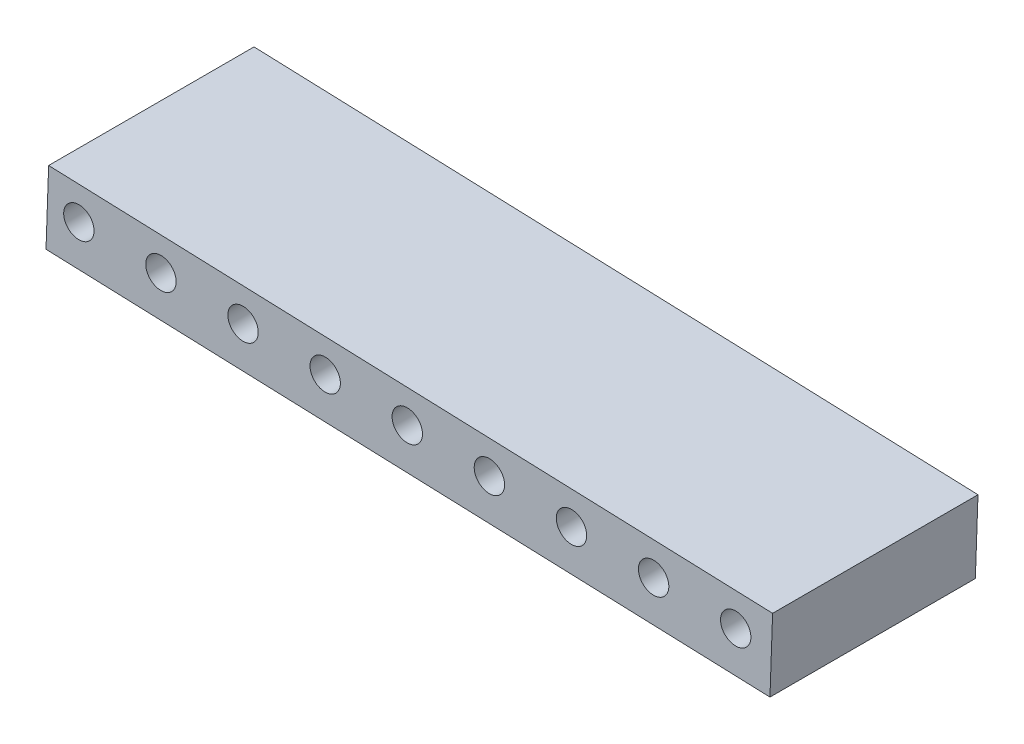
SolidWorks part; units mm, degrees
ref_plane "前视基准面" through (0, 0, 0) normal (0, 0, 1) x (1, 0, 0)
ref_plane "上视基准面" through (0, 0, 0) normal (0, 1, 0) x (1, 0, 0)
ref_plane "右视基准面" through (0, 0, 0) normal (1, 0, 0) x (0, 0, -1)
other "Configuration Table"
sketch "草图1" plane through (0, 0, 0) normal (0, 0, 1) x (1, 0, 0)
  line L0 (0, 0) -> (140, 0)
  line L1 (0, 35) -> (140, 25)
  line L2 (0, -35) -> (140, -25)
  circle A0 centre (0, 0) radius 35
  circle A1 centre (140, 0) radius 25
  dimension "D1" = 70
  dimension "D3" = 50
  dimension "D2" = 140
extrude "凸台-拉伸3" add sketch "草图1" along normal blind 5
sketch "草图4" plane through (0, 0, 5) normal (0, 0, 1) x (1, 0, 0)
  line L1 (-5, -5) -> (5, -5)
  line L2 (-5, -5) -> (-5, 5)
  line L3 (-5, 5) -> (5, 5)
  line L4 (5, -5) -> (5, 5)
  line L5 (-5, -5) -> (5, 5) construction
  line L6 (-5, 5) -> (5, -5) construction
  line L7 (135, -5) -> (145, -5)
  line L8 (135, -5) -> (135, 5)
  line L9 (135, 5) -> (145, 5)
  line L10 (145, -5) -> (145, 5)
  line L11 (135, -5) -> (145, 5) construction
  line L12 (135, 5) -> (145, -5) construction
  circle A0 centre (0, 0) radius 4
  circle A1 centre (-5, 5) radius 1.5
  circle A2 centre (5, 5) radius 1.5
  circle A3 centre (5, -5) radius 1.5
  circle A4 centre (-5, -5) radius 1.5
  circle A5 centre (140, 0) radius 4
  circle A6 centre (135, 5) radius 1.5
  circle A7 centre (145, 5) radius 1.5
  circle A8 centre (145, -5) radius 1.5
  circle A9 centre (135, -5) radius 1.5
  dimension "D1" = 8
  dimension "D4" = 3
  dimension "D6" = 8
  dimension "D9" = 3
  dimension "D2" = 10
  dimension "D3" = 10
  dimension "D7" = 10
  dimension "D8" = 10
  dimension "D5" = 4
  dimension "D10" = 4
extrude "切除-拉伸3" cut sketch "草图4" against normal blind 5 contours A5 | A0 | L2 A4 L1 | L1 A4 L2 | A6 | A9 | A8 | A7 | A1 | A2 | A3
sketch "草图5" plane through (0, 0, 5) normal (0, 0, 1) x (1, 0, 0)
  circle A0 centre (0, 0) radius 11
  circle A1 centre (140, 0) radius 11
  dimension "D1" = 22
  dimension "D2" = 22
extrude "切除-拉伸4" cut sketch "草图5" against normal blind 2
sketch "草图6" plane through (0, 0, 5) normal (0, 0, 1) x (1, 0, 0)
  circle A0 centre (0, 0) radius 30
  circle A1 centre (0, 30) radius 1.5
  circle A2 centre (15, 25.9808) radius 1.5
  circle A3 centre (25.9808, 15) radius 1.5
  circle A4 centre (30, 0) radius 1.5
  circle A5 centre (25.9808, -15) radius 1.5
  circle A6 centre (15, -25.9808) radius 1.5
  circle A7 centre (0, -30) radius 1.5
  circle A8 centre (-15, -25.9808) radius 1.5
  circle A9 centre (-25.9808, -15) radius 1.5
  circle A10 centre (-30, 0) radius 1.5
  circle A11 centre (-25.9808, 15) radius 1.5
  circle A12 centre (-15, 25.9808) radius 1.5
  circle A13 centre (140, 0) radius 20
  circle A14 centre (140, 20) radius 1.5
  circle A15 centre (150, 17.3205) radius 1.5
  circle A16 centre (157.3205, 10) radius 1.5
  circle A17 centre (160, 0) radius 1.5
  circle A18 centre (157.3205, -10) radius 1.5
  circle A19 centre (150, -17.3205) radius 1.5
  circle A20 centre (140, -20) radius 1.5
  circle A21 centre (130, -17.3205) radius 1.5
  circle A22 centre (122.6795, -10) radius 1.5
  circle A23 centre (120, 0) radius 1.5
  circle A24 centre (122.6795, 10) radius 1.5
  circle A25 centre (130, 17.3205) radius 1.5
  point P29 (0, 0)
  dimension "D1" = 60
  dimension "D2" = 3
  dimension "D4" = 40
  dimension "D5" = 3
  dimension "D3" = 12
  dimension "D6" = 12
extrude "切除-拉伸6" cut sketch "草图6" against normal through all contours A0 A12 | A11 | A1 | A2 | A3 | A4 | A5 | A6 | A7 | A8 | A9 | A10 | A25 | A14 | A15 | A16 | A17 | A18 | A19 | A20 | A21 | A22 | A23 | A24
sketch "草图7" plane through (0, 0, 5) normal (0, 0, 1) x (1, 0, 0)
  line L0 (140, 25) -> (0, 20)
  line L1 (140, -25) -> (0, -20)
  circle A0 centre (0, 0) radius 20
  circle A1 centre (140, 0) radius 25
  circle M1 centre (15, -25.9808) radius 1.5
  circle M2 centre (0, -30) radius 1.5
  circle M3 centre (-15, -25.9808) radius 1.5
  circle M4 centre (-25.9808, -15) radius 1.5
  circle M5 centre (-30, 0) radius 1.5
  circle M20 centre (15, 25.9808) radius 1.5
  circle M21 centre (-15, 25.9808) radius 1.5
  circle M22 centre (-25.9808, 15) radius 1.5
  circle M23 centre (0, 30) radius 1.5
  line M27 (0, -35) -> (140, -25)
  line M29 (140, 25) -> (0, 35)
  arc M30 (0, 35) -> (0, -35) centre (0, 0) ccw
  dimension "D1" = 40
extrude "切除-拉伸7" cut sketch "草图7" against normal blind 10 contours A1 L1 A0 L0 M29 M30 M27 M1 M3 M5 M21 M23 M22 M20 M4 M2
sketch "草图8" plane through (0, 0, 5) normal (0, 0, 1) x (1, 0, 0)
  circle A1 centre (0, 0) radius 11
extrude "切除-拉伸8" cut sketch "草图8" against normal blind 10
sketch "草图9" plane through (0, 0, 5) normal (0, 0, 1) x (1, 0, 0)
  circle A0 centre (0, 0) radius 15
  circle A1 centre (0, 15) radius 1.5
  circle A2 centre (10.6066, 10.6066) radius 1.5
  circle A3 centre (15, 0) radius 1.5
  circle A4 centre (10.6066, -10.6066) radius 1.5
  circle A5 centre (0, -15) radius 1.5
  circle A6 centre (-10.6066, -10.6066) radius 1.5
  circle A7 centre (-15, 0) radius 1.5
  circle A8 centre (-10.6066, 10.6066) radius 1.5
  dimension "D1" = 30
  dimension "D2" = 3
  dimension "D3" = 8
extrude "切除-拉伸9" cut sketch "草图9" against normal blind 10 contours A0 A4 | A2 | A3 | A5 | A6 | A7 | A8 | A1
sketch "草图10" plane through (0, 0, 3) normal (0, 0, 1) x (1, 0, 0)
  circle A0 centre (140, 0) radius 5
  dimension "D1" = 10
extrude "切除-拉伸10" cut sketch "草图10" against normal blind 10
sketch "草图11" plane through (0, 0, 5) normal (0, 0, 1) x (1, 0, 0)
  line L0 (140, 0) -> (110, 0)
  line L1 (140, 0) -> (130, 0)
  line L2 (110, 0) -> (105.5, 0)
  line L3 (150, -10) -> (110, -10)
  line L4 (150, -10) -> (150, 10)
  line L5 (150, 10) -> (110, 10)
  line L6 (110, -10) -> (110, 10)
  line L7 (150, -10) -> (110, 10) construction
  line L8 (150, 10) -> (110, -10) construction
  line L9 (105.5, 0) -> (105.5, 5)
  line L10 (130, -1000) -> (130, 49000) construction
  circle A0 centre (105.5, 5) radius 2
  circle A1 centre (105.5, -5) radius 2
  circle A2 centre (154.5, -5) radius 2
  circle A3 centre (154.5, 5) radius 2
  dimension "D6" = 4
  dimension "D1" = 30
  dimension "D2" = 10
  dimension "D3" = 20
  dimension "D4" = 4.5
  dimension "D5" = 5
extrude "切除-拉伸11" cut sketch "草图11" against normal blind 10
sketch "草图12" plane through (0, 0, 5) normal (0, 0, 1) x (1, 0, 0)
  line L0 (110, 10) -> (44831.3595, -22350.6798) construction
  line L1 (150, 10) -> (-44571.3595, -22350.6798) construction
  line L3 (109.5, -11) -> (150.5, -11)
  line L4 (109.5, -11) -> (109.5, 11)
  line L5 (109.5, 11) -> (150.5, 11)
  line L6 (150.5, -11) -> (150.5, 11)
  line L7 (109.5, -11) -> (150.5, 11) construction
  line L8 (109.5, 11) -> (150.5, -11) construction
  point P8 (130, 0)
  dimension "D1" = 41
  dimension "D2" = 22
extrude "切除-拉伸12" cut sketch "草图12" against normal blind 10
sketch "草图13" plane through (0, 0, 5) normal (0, 0, 1) x (1, 0, 0)
  line L0 (0.1785, -15.0032) -> (138.395, -19.9395)
  line L1 (0, -20) -> (138.2166, -24.9363)
  circle A0 centre (0, -15) radius 1.5
  circle A1 centre (9.9936, -15.3569) radius 1.5
  circle A2 centre (19.9873, -15.7138) radius 1.5
  circle A3 centre (29.9809, -16.0707) radius 1.5
  circle A4 centre (39.9745, -16.4277) radius 1.5
  circle A5 centre (49.9681, -16.7846) radius 1.5
  circle A6 centre (59.9618, -17.1415) radius 1.5
  circle A7 centre (69.9554, -17.4984) radius 1.5
  circle A8 centre (79.949, -17.8553) radius 1.5
  circle A9 centre (89.9427, -18.2122) radius 1.5
  circle A10 centre (99.9363, -18.5692) radius 1.5
  circle A11 centre (109.9299, -18.9261) radius 1.5
  circle A12 centre (119.9235, -19.283) radius 1.5
  circle A13 centre (129.9172, -19.6399) radius 1.5
  circle A14 centre (139.9108, -19.9968) radius 1.5
  circle M27 centre (130, -17.3205) radius 1.5
  dimension "D1" = 5
  dimension "D2" = 15
extrude "切除-拉伸13" cut sketch "草图13" against normal blind 10 contours L0 A1 | L0 A1 | L0 A13 | A13 L0 M27 | A2 | A3 | A4 | A5 | A6 | A7 | A9 | A8 | A10 | A11 | A12
sketch "草图14" plane through (0, 0, 5) normal (0, 0, 1) x (1, 0, 0)
  circle A0 centre (130, -17.3205) radius 1.5
  circle A1 centre (129.9172, -19.6399) radius 1.5
extrude "凸台-拉伸4" add sketch "草图14" against normal blind 5 contours A1 A0
sketch "草图15" plane through (0, 0, 5) normal (0, 0, 1) x (1, 0, 0)
  circle A0 centre (25.9808, 15) radius 1.5
  circle A1 centre (30, 0) radius 1.5
  circle A2 centre (25.9808, -15) radius 1.5
extrude "凸台-拉伸6" add sketch "草图15" against normal blind 5
sketch "草图16" plane through (0, 0, 5) normal (0, 0, 1) x (1, 0, 0)
  line L0 (0, 20) -> (140, 25)
  line L1 (0.1785, 15.0032) -> (140.1785, 20.0032)
  arc A0 (138.2166, -24.9363) -> (138.2166, 24.9363) centre (140, 0) ccw construction
  circle A1 centre (0, 15) radius 1.5
  circle A2 centre (9.9936, 15.3569) radius 1.5
  circle A3 centre (19.9873, 15.7138) radius 1.5
  circle A4 centre (29.9809, 16.0707) radius 1.5
  circle A5 centre (39.9745, 16.4277) radius 1.5
  circle A6 centre (49.9681, 16.7846) radius 1.5
  circle A7 centre (59.9618, 17.1415) radius 1.5
  circle A8 centre (69.9554, 17.4984) radius 1.5
  circle A9 centre (79.949, 17.8553) radius 1.5
  circle A10 centre (89.9427, 18.2122) radius 1.5
  circle A11 centre (99.9363, 18.5692) radius 1.5
  circle A12 centre (109.9299, 18.9261) radius 1.5
  circle A13 centre (119.9235, 19.283) radius 1.5
  circle A14 centre (129.9172, 19.6399) radius 1.5
  circle A15 centre (139.9108, 19.9968) radius 1.5
  dimension "D1" = 5
  dimension "D2" = 15
extrude "切除-拉伸14" cut sketch "草图16" against normal blind 5 contours L1 A6 | L1 A6 | L1 A7 | L1 A7 | L1 A8 | L1 A8 | A2 | A3 | A4 | A5 | A9 | A10 | A11 | A12 | A13 | A14
sketch "草图17" plane through (0, 0, 5) normal (0, 0, 1) x (1, 0, 0)
  circle A0 centre (130, 17.3205) radius 1.5
  circle A1 centre (129.9172, 19.6399) radius 1.5
extrude "凸台-拉伸7" add sketch "草图17" against normal blind 5 contours A1 A0
sketch "草图18" plane through (0, 0, 5) normal (0, 0, 1) x (1, 0, 0)
  line L2 (138.5735, 14.9427) -> (0.3569, 10.0064)
  line L3 (138.5735, 14.9427) -> (0.3569, 10.0064)
  line L5 (138.5735, -14.9427) -> (0.3569, -10.0064)
  line L6 (138.5735, -14.9427) -> (0.3569, -10.0064)
  circle A0 centre (0, 0) radius 25
  circle A1 centre (0, 0) radius 100
  dimension "D1" = 50
  dimension "D2" = 200
  dimension "D3" = 10
  dimension "D4" = 10
extrude "切除-拉伸15" cut sketch "草图18" against normal blind 5 contours L6 A1 L3 A0
sketch "草图19" plane through (0, 0, 5) normal (0, 0, 1) x (1, 0, 0)
  line L2 (99.0445, 14.5316) -> (22.5117, 11.7983)
  line L3 (134.9707, 15.8146) -> (6.5499, 11.2282)
  line L4 (16.3089, 11.5767) -> (15.9877, 20.571)
  line L5 (99.0445, -14.5316) -> (22.5117, -11.7983)
  line L6 (134.4063, -15.7945) -> (10.6063, -11.3731)
  line L7 (138.2166, 24.9363) -> (0, 20) construction
  line L8 (16.3089, -11.5767) -> (15.9877, -20.571)
  line L9 (138.2166, -24.9363) -> (0, -20) construction
  line L10 (15.9877, -20.571) -> (0, -20)
  line L11 (15.9877, 20.571) -> (0, 20)
  circle A1 centre (140, 0) radius 16.7558
  circle A2 centre (0, 0) radius 20
  dimension "D1" = 1
  dimension "D2" = 1
extrude "切除-拉伸19" cut sketch "草图19" against normal blind 5
sketch "草图21" plane through (0, 0, 5) normal (0, 0, 1) x (1, 0, 0)
  line L0 (134.4063, 15.7945) -> (134.0851, 24.7888)
  line L1 (138.2166, 24.9363) -> (15.9877, 20.571) construction
  line L2 (134.4063, -15.7945) -> (134.0851, -24.7888)
  line L3 (138.2166, -24.9363) -> (15.9877, -20.571) construction
  circle A0 centre (140, 0) radius 25
  arc M1 (156.2593, 4.0487) -> (156.2593, -4.0487) centre (140, 0) cw
  arc M2 (156.2593, -4.0487) -> (155.299, -6.8335) centre (154.5, -5) cw
  arc M3 (155.299, -6.8335) -> (134.4063, -15.7945) centre (140, 0) cw
  line M6 (15.9877, -20.571) -> (138.2166, -24.9363)
  arc M7 (138.2166, -24.9363) -> (138.2166, 24.9363) centre (140, 0) ccw
  line M8 (138.2166, 24.9363) -> (15.9877, 20.571)
  arc M11 (134.4063, 15.7945) -> (155.299, 6.8335) centre (140, 0) cw
  arc M12 (155.299, 6.8335) -> (156.2593, 4.0487) centre (154.5, 5) cw
  circle M37 centre (140, 20) radius 1.5
  circle M38 centre (150, 17.3205) radius 1.5
  circle M39 centre (157.3205, 10) radius 1.5
  circle M40 centre (160, 0) radius 1.5
  circle M41 centre (157.3205, -10) radius 1.5
  circle M42 centre (150, -17.3205) radius 1.5
  circle M43 centre (140, -20) radius 1.5
extrude "切除-拉伸20" cut sketch "草图21" against normal blind 5 contours A0 L0 L2 M7 M11 M12 M1 M2 M3 M38 M40 M42 M43 M41 M39 M37 | A0 L0 M8 | A0 L2 M6
sketch "草图22" plane through (0, 0, 0) normal (0, 0, -1) x (-1, 0, 0)
  line L0 (-134.0851, 24.7888) -> (-134.4063, 15.7945)
  line L1 (-134.4063, 15.7945) -> (-16.3089, 11.5767)
  line L2 (-16.3089, 11.5767) -> (-15.9877, 20.571)
  line L3 (-15.9877, 20.571) -> (-134.0851, 24.7888)
  line L4 (-134.4063, -15.7945) -> (-134.0851, -24.7888)
  line L5 (-134.0851, -24.7888) -> (-15.9877, -20.571)
  line L6 (-15.9877, -20.571) -> (-16.3089, -11.5767)
  line L7 (-16.3089, -11.5767) -> (-134.4063, -15.7945)
extrude "凸台-拉伸8" add sketch "草图22" along normal blind 10
sketch "草图23" plane through (0, 0, 5) normal (0, 0, 1) x (1, 0, 0)
  circle A0 centre (19.9873, 15.7138) radius 1.5
  circle A1 centre (29.9809, 16.0707) radius 1.5
  circle A2 centre (39.9745, 16.4277) radius 1.5
  circle A3 centre (49.9681, 16.7846) radius 1.5
  circle A4 centre (59.9618, 17.1415) radius 1.5
  circle A5 centre (69.9554, 17.4984) radius 1.5
  circle A6 centre (79.949, 17.8553) radius 1.5
  circle A7 centre (89.9427, 18.2122) radius 1.5
  circle A8 centre (99.9363, 18.5692) radius 1.5
  circle A9 centre (109.9299, 18.9261) radius 1.5
  circle A10 centre (119.9235, 19.283) radius 1.5
  circle A11 centre (129.9172, 19.6399) radius 1.5
  circle A12 centre (129.9172, -19.6399) radius 1.5
  circle A13 centre (119.9235, -19.283) radius 1.5
  circle A14 centre (109.9299, -18.9261) radius 1.5
  circle A15 centre (99.9363, -18.5692) radius 1.5
  circle A16 centre (89.9427, -18.2122) radius 1.5
  circle A17 centre (79.949, -17.8553) radius 1.5
  circle A18 centre (69.9554, -17.4984) radius 1.5
  circle A19 centre (59.9618, -17.1415) radius 1.5
  circle A20 centre (49.9681, -16.7846) radius 1.5
  circle A21 centre (39.9745, -16.4277) radius 1.5
  circle A22 centre (29.9809, -16.0707) radius 1.5
  circle A23 centre (19.9873, -15.7138) radius 1.5
extrude "切除-拉伸21" cut sketch "草图23" against normal blind 15
sketch "草图24" plane through (0, 0, -10) normal (0, 0, -1) x (-1, 0, 0)
  line L0 (-134.0851, 24.7888) -> (-134.4063, 15.7945)
  line L1 (-134.4063, 15.7945) -> (-16.3089, 11.5767)
  line L2 (-16.3089, 11.5767) -> (-15.9877, 20.571)
  line L3 (-15.9877, 20.571) -> (-134.0851, 24.7888)
  line L4 (-134.4063, -15.7945) -> (-134.0851, -24.7888)
  line L5 (-134.0851, -24.7888) -> (-15.9877, -20.571)
  line L6 (-15.9877, -20.571) -> (-16.3089, -11.5767)
  line L7 (-16.3089, -11.5767) -> (-134.4063, -15.7945)
  circle A0 centre (-129.9172, 19.6399) radius 1.5
  circle A1 centre (-119.9235, 19.283) radius 1.5
  circle A2 centre (-109.9299, 18.9261) radius 1.5
  circle A3 centre (-99.9363, 18.5692) radius 1.5
  circle A4 centre (-89.9427, 18.2122) radius 1.5
  circle A5 centre (-79.949, 17.8553) radius 1.5
  circle A6 centre (-69.9554, 17.4984) radius 1.5
  circle A7 centre (-59.9618, 17.1415) radius 1.5
  circle A8 centre (-49.9681, 16.7846) radius 1.5
  circle A9 centre (-39.9745, 16.4277) radius 1.5
  circle A10 centre (-29.9809, 16.0707) radius 1.5
  circle A11 centre (-19.9873, 15.7138) radius 1.5
  circle A12 centre (-19.9873, -15.7138) radius 1.5
  circle A13 centre (-29.9809, -16.0707) radius 1.5
  circle A14 centre (-39.9745, -16.4277) radius 1.5
  circle A15 centre (-49.9681, -16.7846) radius 1.5
  circle A16 centre (-59.9618, -17.1415) radius 1.5
  circle A17 centre (-69.9554, -17.4984) radius 1.5
  circle A18 centre (-79.949, -17.8553) radius 1.5
  circle A19 centre (-89.9427, -18.2122) radius 1.5
  circle A20 centre (-99.9363, -18.5692) radius 1.5
  circle A21 centre (-109.9299, -18.9261) radius 1.5
  circle A22 centre (-119.9235, -19.283) radius 1.5
  circle A23 centre (-129.9172, -19.6399) radius 1.5
extrude "凸台-拉伸9" add sketch "草图24" along normal blind 10
sketch "草图25" plane through (0, 0, 5) normal (0, 0, 1) x (1, 0, 0)
  line L1 (-124.8837, 76.8394) -> (141.949, 76.8394)
  line L2 (-124.8837, 76.8394) -> (-124.8837, 4.7367)
  line L3 (-124.8837, 4.7367) -> (141.949, 4.7367)
  line L4 (141.949, 76.8394) -> (141.949, 4.7367)
  line L5 (-124.8837, 76.8394) -> (141.949, 4.7367) construction
  line L6 (-124.8837, 4.7367) -> (141.949, 76.8394) construction
  point P0 (8.5326, 40.788)
extrude "切除-拉伸22" cut sketch "草图25" against normal through all
sketch "草图27" plane through (0, 0, -20) normal (0, 0, -1) x (-1, 0, 0)
  line L0 (-129.9172, -19.6399) -> (49838.2255, 1764.9366) construction
  circle A0 centre (-129.9172, -19.6399) radius 1.85
  circle A1 centre (-119.9235, -19.283) radius 1.85
  circle A2 centre (-109.9299, -18.9261) radius 1.85
  circle A3 centre (-99.9363, -18.5692) radius 1.85
  circle A4 centre (-89.9427, -18.2122) radius 1.85
  circle A5 centre (-79.949, -17.8553) radius 1.85
  circle A6 centre (-69.9554, -17.4984) radius 1.85
  circle A7 centre (-59.9618, -17.1415) radius 1.85
  circle A8 centre (-49.9681, -16.7846) radius 1.85
  circle A9 centre (-39.9745, -16.4277) radius 1.85
  circle A10 centre (-29.9809, -16.0707) radius 1.85
  circle A11 centre (-19.9873, -15.7138) radius 1.85
  dimension "D1" = 3.7
  dimension "D2" = 12
extrude "切除-拉伸23" cut sketch "草图27" against normal through all
sketch "草图28" plane through (0, 0, 5) normal (0, 0, 1) x (1, 0, 0)
  line L0 (16.3089, -11.5767) -> (15.9877, -20.571)
  line L1 (36.2961, -12.2906) -> (35.9749, -21.2848)
  line L2 (16.3089, -11.5767) -> (36.2961, -12.2906)
  line L3 (15.9877, -20.571) -> (35.9749, -21.2848)
  dimension "D1" = 20
sketch "草图29" plane through (0, 0, 5) normal (0, 0, 1) x (1, 0, 0)
  line L0 (134.4063, -15.7945) -> (134.0851, -24.7888)
  line L1 (114.419, -15.0807) -> (114.0978, -24.0749)
  line L2 (114.419, -15.0807) -> (134.4063, -15.7945)
  line L3 (114.0978, -24.0749) -> (134.0851, -24.7888)
  dimension "D1" = 20
extrude "切除-拉伸25" cut sketch "草图29" against normal through all both and the other way through all
sketch "草图30" plane through (0, 0, -20) normal (0, 0, -1) x (-1, 0, 0)
  line L0 (-35.9749, -21.2848) -> (-36.2961, -12.2906)
  line L1 (-36.2961, -12.2906) -> (-16.3089, -11.5767)
  line L2 (-16.3089, -11.5767) -> (-15.9877, -20.571)
  line L3 (-15.9877, -20.571) -> (-35.9749, -21.2848)
  line L4 (-25.9813, -20.9279) -> (-26.3025, -11.9336)
  line M7 (-15.9877, -20.571) -> (-16.3089, -11.5767)
  line M8 (-16.3089, -11.5767) -> (-114.419, -15.0807)
  circle M18 centre (-19.9873, -15.7138) radius 1.85
extrude "切除-拉伸27" cut sketch "草图30" against normal blind 25 contours L4 L3 M7 M8 M18
